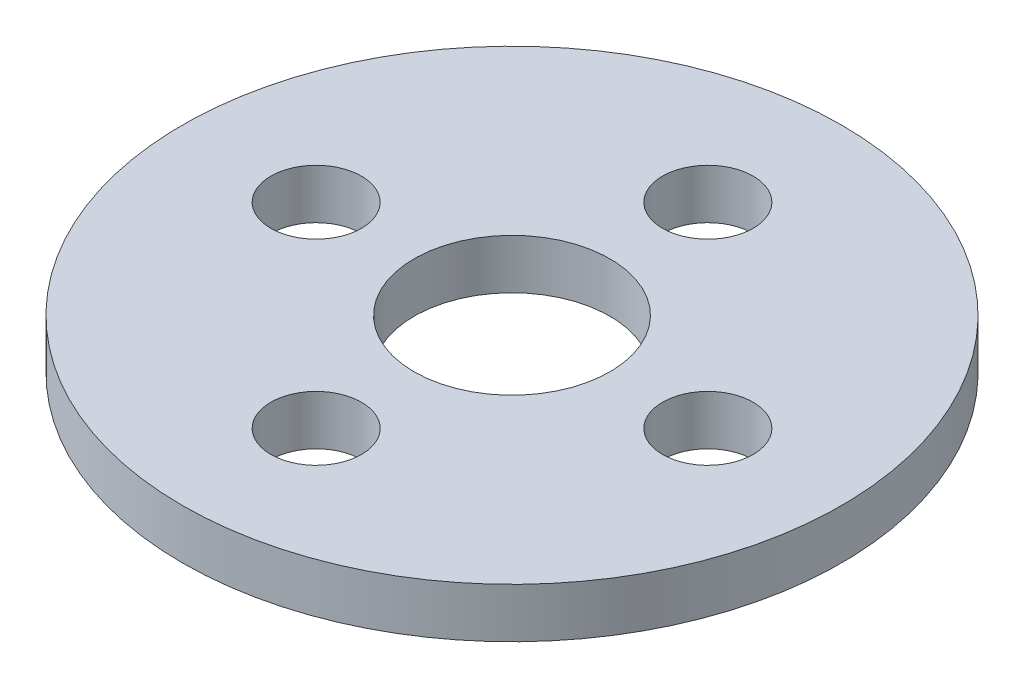
SolidWorks part; units mm, degrees
ref_plane "Front Plane" through (0, 0, 0) normal (0, 0, 1) x (1, 0, 0)
ref_plane "Top Plane" through (0, 0, 0) normal (0, 1, 0) x (1, 0, 0)
ref_plane "Right Plane" through (0, 0, 0) normal (1, 0, 0) x (0, 0, -1)
sketch "Sketch1" plane through (0, 0, 0) normal (0, 1, 0) x (1, 0, 0)
  circle A0 centre (0, 0) radius 13.462
  circle B0 centre (0, 0) radius 4
  circle B1 centre (8, 0) radius 1.85
  circle B2 centre (-8, 0) radius 1.85
  circle B3 centre (0, -8) radius 1.85
  circle B4 centre (0, 8) radius 1.85
sketch_block_instance "Block4-1"
sketch_block "Block4" parameters "D1"=3.7, "D2"=8, "D3"=16
extrude "Boss-Extrude1" add sketch "Sketch1" along normal blind 2.032
